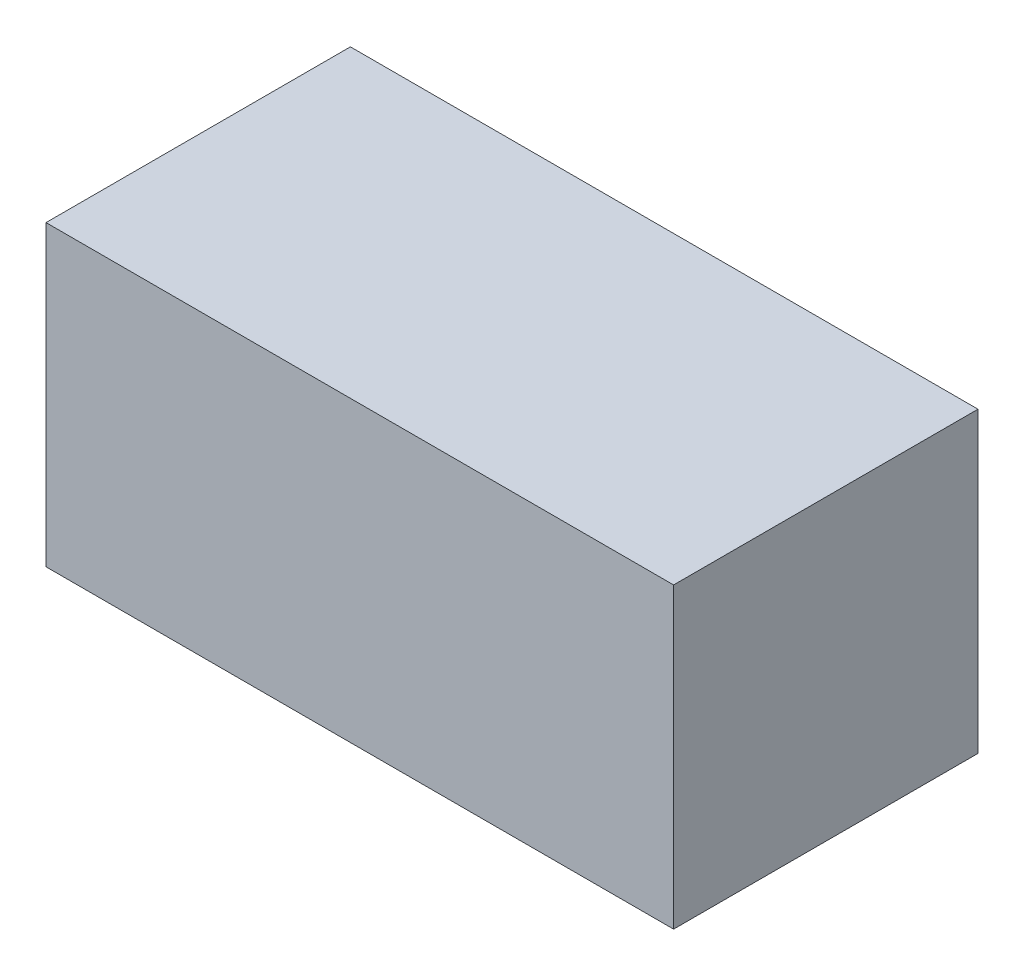
SolidWorks part; units mm, degrees
material "ABS PC"
ref_plane "Front Plane" through (0, 0, 0) normal (0, 0, 1) x (1, 0, 0)
ref_plane "Top Plane" through (0, 0, 0) normal (0, 1, 0) x (1, 0, 0)
ref_plane "Right Plane" through (0, 0, 0) normal (1, 0, 0) x (0, 0, -1)
sketch "Sketch1" plane through (0, 0, 0) normal (0, 0, 1) x (1, 0, 0)
  line L1 (0, 0) -> (200, 0)
  line L2 (0, 0) -> (0, 95)
  line L3 (0, 95) -> (200, 95)
  line L4 (200, 0) -> (200, 95)
  dimension "D1" = 200
  dimension "D2" = 95
extrude "Boss-Extrude1" add sketch "Sketch1" along normal blind 97
